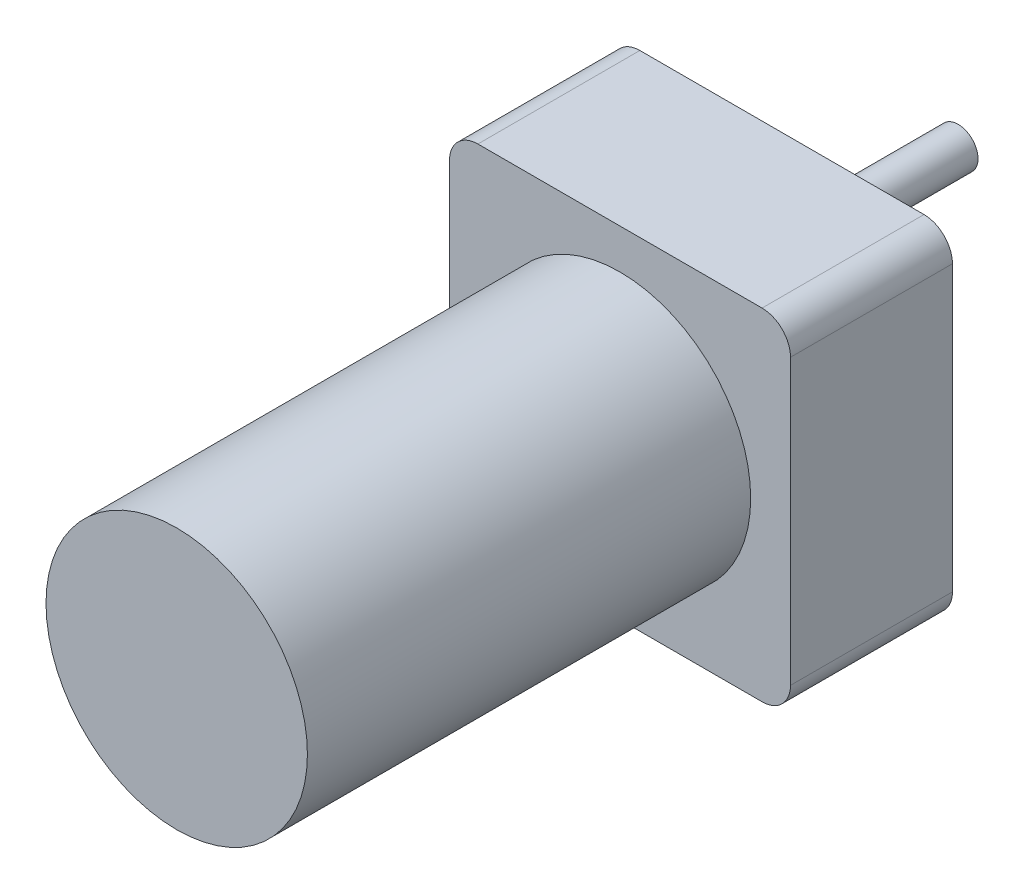
SolidWorks part; units mm, degrees
ref_plane "Front Plane" through (0, 0, 0) normal (0, 0, 1) x (1, 0, 0)
ref_plane "Top Plane" through (0, 0, 0) normal (0, 1, 0) x (1, 0, 0)
ref_plane "Right Plane" through (0, 0, 0) normal (1, 0, 0) x (0, 0, -1)
sketch "Sketch1" plane through (0, 0, 0) normal (0, 0, 1) x (1, 0, 0)
  line L1 (5, 0) -> (55, 0)
  line L2 (0, 5) -> (0, 55)
  line L3 (5, 60) -> (55, 60)
  line L4 (60, 5) -> (60, 55)
  arc A0 (0, 55) -> (5, 60) centre (5, 55) cw
  arc A1 (60, 55) -> (55, 60) centre (55, 55) ccw
  arc A2 (55, 0) -> (60, 5) centre (55, 5) ccw
  arc A3 (0, 5) -> (5, 0) centre (5, 5) ccw
  point P7 (0, 60)
  point P10 (60, 60)
  point P13 (60, 0)
  point P16 (0, 0)
  dimension "D3" = 5
  dimension "D4" = 5
  dimension "D5" = 5
  dimension "D6" = 5
  dimension "D1" = 60
  dimension "D2" = 60
extrude "Boss-Extrude1" add sketch "Sketch1" along normal blind 28.5
sketch "Sketch2" plane through (0, 0, 28.5) normal (0, 0, 1) x (1, 0, 0)
  line L0 (5, 0) -> (55, 0) construction
  line L1 (0, 55) -> (0, 5) construction
  circle A0 centre (30, 30) radius 23
  dimension "D1" = 46
  dimension "D2" = 30
  dimension "D3" = 30
extrude "Boss-Extrude2" add sketch "Sketch2" along normal blind 78
sketch "Sketch3" plane through (0, 0, 0) normal (0, 0, -1) x (-1, 0, 0)
  line L0 (-55, 60) -> (-5, 60) construction
  line L3 (-60, 5) -> (-60, 55) construction
  circle A0 centre (-30, 40) radius 9.125
  dimension "D2" = 18.25
  dimension "D3" = 30
  dimension "D1" = 20
extrude "Boss-Extrude3" add sketch "Sketch3" along normal blind 6
sketch "Sketch4" plane through (0, 0, -6) normal (0, 0, -1) x (-1, 0, 0)
  line L0 (-55, 60) -> (-5, 60) construction
  line L2 (-60, 5) -> (-60, 55) construction
  circle A0 centre (-30, 42.25) radius 3.5
  dimension "D1" = 7
  dimension "D2" = 30
  dimension "D3" = 17.75
extrude "Boss-Extrude4" add sketch "Sketch4" along normal blind 25
sketch "Sketch5" plane through (0, 0, -31) normal (0, 0, -1) x (-1, 0, 0)
  line L0 (-32.5, 39.8005) -> (-27.5, 39.8005)
  circle A1 centre (-30, 42.25) radius 3.5 construction
  arc A2 (-32.5, 39.8005) -> (-27.5, 39.8005) centre (-30, 42.25) ccw
  dimension "D2" = 5
extrude "Cut-Extrude1" cut sketch "Sketch5" against normal blind 18
sketch "Sketch6" plane through (0, 0, 0) normal (0, 0, -1) x (-1, 0, 0)
  line L1 (-60, 5) -> (-60, 55) construction
  line L2 (-55, 60) -> (-5, 60) construction
  line L3 (0, 55) -> (0, 5) construction
  circle A0 centre (-54.75, 54.75) radius 2.4
  circle A1 centre (-5.25, 54.75) radius 2.4
  circle A2 centre (-5.25, 5.25) radius 2.4
  circle A3 centre (-54.75, 5.25) radius 2.4
  dimension "D1" = 49.5
  dimension "D2" = 49.5
  dimension "D3" = 49.5
  dimension "D4" = 49.5
  dimension "D5" = 4.8
  dimension "D6" = 4.8
  dimension "D7" = 4.8
  dimension "D8" = 4.8
  dimension "D9" = 5.25
  dimension "D10" = 5.25
  dimension "D11" = 5.25
  dimension "D12" = 5.25
extrude "Cut-Extrude2" cut sketch "Sketch6" against normal blind 10
sketch "Sketch7" plane through (0, 0, 0) normal (0, 0, -1) x (-1, 0, 0)
  circle A0 centre (-30, 40) radius 12.5
  circle A1 centre (-30, 40) radius 9.125
  dimension "D1" = 25
  dimension "D2" = 18.25
extrude "Boss-Extrude5" add sketch "Sketch7" along normal blind 3
